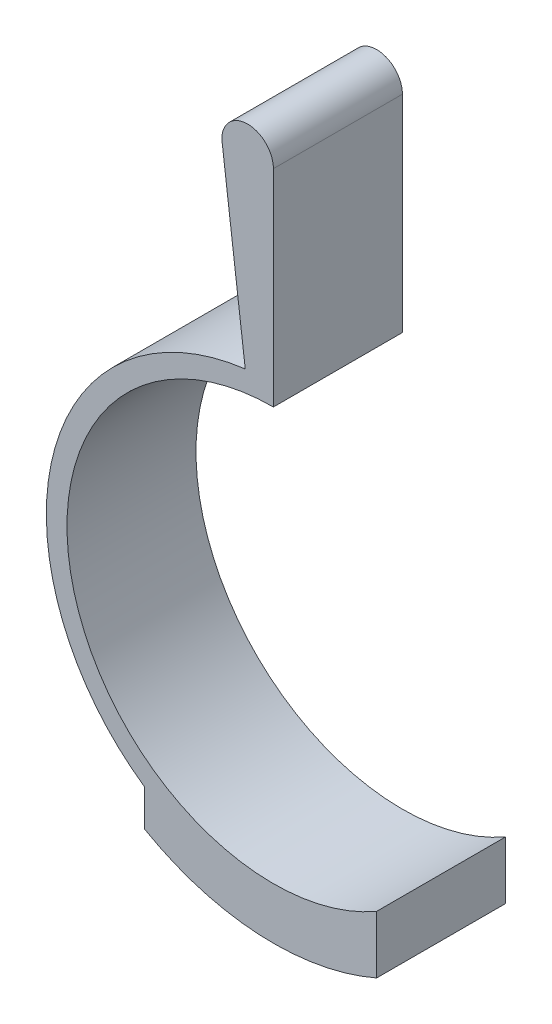
SolidWorks part; units mm, degrees
ref_plane "Plano frontal" through (0, 0, 0) normal (0, 0, 1) x (1, 0, 0)
ref_plane "Plano superior" through (0, 0, 0) normal (0, 1, 0) x (1, 0, 0)
ref_plane "Plano direito" through (0, 0, 0) normal (1, 0, 0) x (0, 0, -1)
sketch "Esboço1" plane through (0, 0, 0) normal (0, 0, 1) x (1, 0, 0)
  line L0 (0, 0) -> (10, 0) construction
  line L1 (0, 0) -> (-10, 0) construction
  line L2 (-10, 0) -> (-10, -17.3205) construction
  line L3 (10, -17.3205) -> (10, -22.9129)
  line L6 (0, 20) -> (0, 40)
  line L7 (-5, 40) -> (-2.7288, 21.8301)
  line L8 (-12.5, -18.1039) -> (-12.5, -21.6506)
  arc A0 (0, 20) -> (10, -17.3205) centre (0, 0) ccw
  arc A1 (-2.7288, 21.8301) -> (-12.5, -18.1039) centre (0, 0) ccw
  arc A2 (0, 25) -> (-3.1009, 24.8069) centre (0, 0) ccw construction
  arc A3 (0, 40) -> (-4.9231, 39.3846) centre (-2.5, 40) ccw
  arc A4 (-12.5, -21.6506) -> (10, -22.9129) centre (0, 0) ccw
  dimension "D1" = 50
  dimension "D2" = 20
  dimension "D3" = 10
  dimension "D4" = 5
extrude "Ressalto-extrusão1" add sketch "Esboço1" along normal blind 12.5
